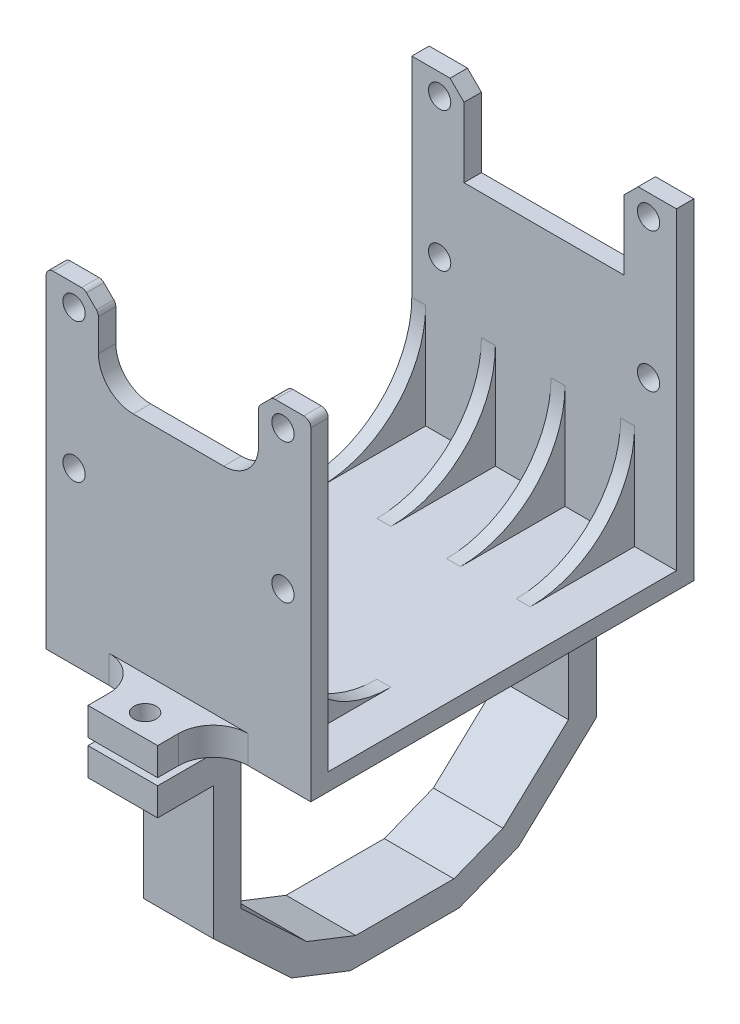
SolidWorks part; units mm, degrees
ref_plane "前视基准面" through (0, 0, 0) normal (0, 0, 1) x (1, 0, 0)
ref_plane "上视基准面" through (0, 0, 0) normal (0, 1, 0) x (1, 0, 0)
ref_plane "右视基准面" through (0, 0, 0) normal (1, 0, 0) x (0, 0, -1)
sketch "草图1" plane through (0, 0, 0) normal (0, 0, 1) x (1, 0, 0)
  line L1 (-19.3201, 24.1356) -> (18.6799, 24.1356)
  line L2 (-19.3201, 24.1356) -> (-19.3201, -20.8644)
  line L3 (-19.3201, -20.8644) -> (18.6799, -20.8644)
  line L4 (18.6799, 24.1356) -> (18.6799, -20.8644)
  circle A0 centre (-15.3201, 21.1356) radius 1.6
  circle A1 centre (14.6799, 21.1356) radius 1.6
  circle A2 centre (-15.3201, 1.1356) radius 1.6
  circle A3 centre (14.6799, 1.1356) radius 1.6
  dimension "D3" = 30
  dimension "D4" = 30
  dimension "D5" = 20
  dimension "D6" = 3.2
  dimension "D7" = 3.2
  dimension "D8" = 3.2
  dimension "D9" = 3.2
  dimension "D10" = 4
  dimension "D11" = 4
  dimension "D12" = 3
  dimension "D13" = 3
  dimension "D1" = 38
  dimension "D2" = 45
extrude "凸台-拉伸1" add sketch "草图1" along normal blind 2.5
sketch "草图2" plane through (0, 0, 2.5) normal (0, 0, 1) x (1, 0, 0)
  line L0 (18.6799, 24.1356) -> (-19.3201, 24.1356) construction
  line L1 (-11.8201, 24.1356) -> (11.1799, 24.1356)
  line L2 (-11.8201, 22.1356) -> (-11.8201, 12.1356)
  line L3 (-11.8201, 12.1356) -> (11.1799, 12.1356)
  line L4 (11.1799, 22.1356) -> (11.1799, 12.1356)
  line L5 (-13.8201, 24.1356) -> (-11.8201, 22.1356)
  line L6 (-11.8201, 24.1356) -> (-13.8201, 24.1356)
  line L7 (11.1799, 22.1356) -> (13.1799, 24.1356)
  line L8 (13.1799, 24.1356) -> (11.1799, 24.1356)
  circle A0 centre (-15.3201, 21.1356) radius 1.6 construction
  circle A1 centre (14.6799, 21.1356) radius 1.6 construction
  dimension "D2" = 3.5
  dimension "D1" = 3.5
  dimension "D3" = 12
  dimension "D4" = 2
  dimension "D5" = 2
  dimension "D6" = 2
  dimension "D7" = 2
extrude "切除-拉伸1" cut sketch "草图2" against normal blind 2.5
sketch "草图3" plane through (0, -20.8644, 0) normal (0, -1, 0) x (1, 0, 0)
  line L0 (18.6799, 2.5) -> (18.6799, 0) construction
  line L1 (-19.3201, 2.5) -> (18.6799, 2.5)
  line L2 (-19.3201, 2.5) -> (-19.3201, -52.5)
  line L3 (-19.3201, -52.5) -> (18.6799, -52.5)
  line L4 (18.6799, 2.5) -> (18.6799, -52.5)
  dimension "D1" = 55
extrude "凸台-拉伸2" add sketch "草图3" along normal blind 2.5
fillet "圆角3" radius 1 6 edges at (11.1799, 22.1356, 1.25) (13.1799, 24.1356, 1.25) (-19.3201, 24.1356, 1.25) (18.6799, 24.1356, 1.25) (-11.8201, 22.1356, 1.25) (-13.8201, 24.1356, 1.25)
fillet "Fillet1" radius 5 2 edges at (-11.8201, 12.1356, 1.25) (11.1799, 12.1356, 1.25)
sketch "Sketch4" plane through (-19.3201, 0, 0) normal (-1, 0, 0) x (0, 0, 1)
  line L0 (0, -5.8644) -> (0, -20.8644)
  line L1 (0, 23.1356) -> (0, -20.8644) construction
  line L2 (0, -20.8644) -> (-15, -20.8644)
  line L3 (0, -20.8644) -> (-52.5, -20.8644) construction
  arc A0 (0, -5.8644) -> (-15, -20.8644) centre (-15, -5.8644) cw
  dimension "D1" = 15
extrude "Extrude3" add sketch "Sketch4" against normal blind 2
ref_plane "Plane1" through (0, 0, -25) normal (0, 0, -1) x (-1, 0, 0)
mirror "Mirror1" about plane through (0, 0, -25) normal (0, 0, -1) of "凸台-拉伸1"
mirror "Mirror2" about plane through (0, 0, -25) normal (0, 0, -1) of "切除-拉伸1"
pattern_linear "LPattern1" count 4 spacing 10 along (1, 0, 0) of "Extrude3"
mirror "Mirror3" about plane through (0, 0, -25) normal (0, 0, -1) of "LPattern1", "Extrude3"
ref_plane "Plane2" through (-0.3201, 0, 0) normal (-1, 0, 0) x (0, 0, 1)
sketch "Sketch5" plane through (-0.3201, 0, 0) normal (-1, 0, 0) x (0, 0, 1)
  line L0 (-48.5, -23.3644) -> (-48.5, -45.6488)
  line L1 (2.5, -23.3644) -> (-52.5, -23.3644) construction
  line L2 (-48.5, -45.6488) -> (-39.0953, -54.4416)
  line L3 (-39.0953, -54.4416) -> (-32.0493, -57.2068)
  line L4 (-32.0493, -57.2068) -> (-17.9507, -57.2068)
  line L5 (-25, -23.3644) -> (-25, -57.2068) construction
  line L6 (-7.5, -23.3644) -> (-42.5, -23.3644) construction
  line L7 (-48.5, -23.3644) -> (-52.5, -23.3644)
  line L8 (-52.5, -23.3644) -> (-52.5, -47.385)
  line L9 (-52.5, -47.385) -> (-41.2684, -57.8857)
  line L10 (-41.2684, -57.8857) -> (-32.8061, -61.2068)
  line L11 (-32.8061, -61.2068) -> (-17.1939, -61.2068)
  line L12 (-8.7316, -57.8857) -> (-17.1939, -61.2068)
  line L13 (2.5, -47.385) -> (-8.7316, -57.8857)
  line L14 (2.5, -28.3644) -> (2.5, -47.385)
  line L16 (-10.9047, -54.4416) -> (-17.9507, -57.2068)
  line L17 (-1.5, -45.6488) -> (-10.9047, -54.4416)
  line L18 (-1.5, -24.3644) -> (-1.5, -45.6488)
  line L19 (-1.5, -24.3644) -> (10.5, -24.3644)
  line L20 (10.5, -24.3644) -> (10.5, -28.3644)
  line L21 (10.5, -28.3644) -> (2.5, -28.3644)
  line L22 (2.5, -23.3644) -> (10.5, -23.3644)
  line L23 (10.5, -23.3644) -> (10.5, -19.3644)
  line L24 (10.5, -19.3644) -> (2.5, -19.3644)
  line L25 (2.5, 23.1356) -> (2.5, -23.3644) construction
  line L26 (2.5, -19.3644) -> (2.5, -23.3644)
  point P16 (-25, -57.2068)
  point P23 (-25, -61.2068)
  dimension "D1" = 4
  dimension "D2" = 4
  dimension "D3" = 4
  dimension "D4" = 4
  dimension "D5" = 22.2844
  dimension "D6" = 12.8749
  dimension "D7" = 133.074
  dimension "D8" = 7.5692
  dimension "D9" = 158.354
  dimension "D10" = 4
  dimension "D11" = 1
  dimension "D12" = 8
  dimension "D13" = 4
extrude "Extrude4" add sketch "Sketch5" along normal blind 5 and the other way blind 5
sketch "Sketch6" plane through (0, -28.3644, 0) normal (0, -1, 0) x (1, 0, 0)
  line L0 (4.6799, 10.5) -> (-5.3201, 10.5) construction
  circle A0 centre (-0.3201, 7.3) radius 1.6
  dimension "D1" = 3.2
  dimension "D2" = 3.2
extrude "Cut-Extrude1" cut sketch "Sketch6" against normal blind 20
fillet "Fillet2" radius 5 2 edges at (4.6799, -23.3644, -50.5) (-5.3201, -23.3644, -50.5)
fillet "Fillet3" radius 5 2 edges at (4.6799, -21.3644, 2.5) (-5.3201, -21.3644, 2.5)
